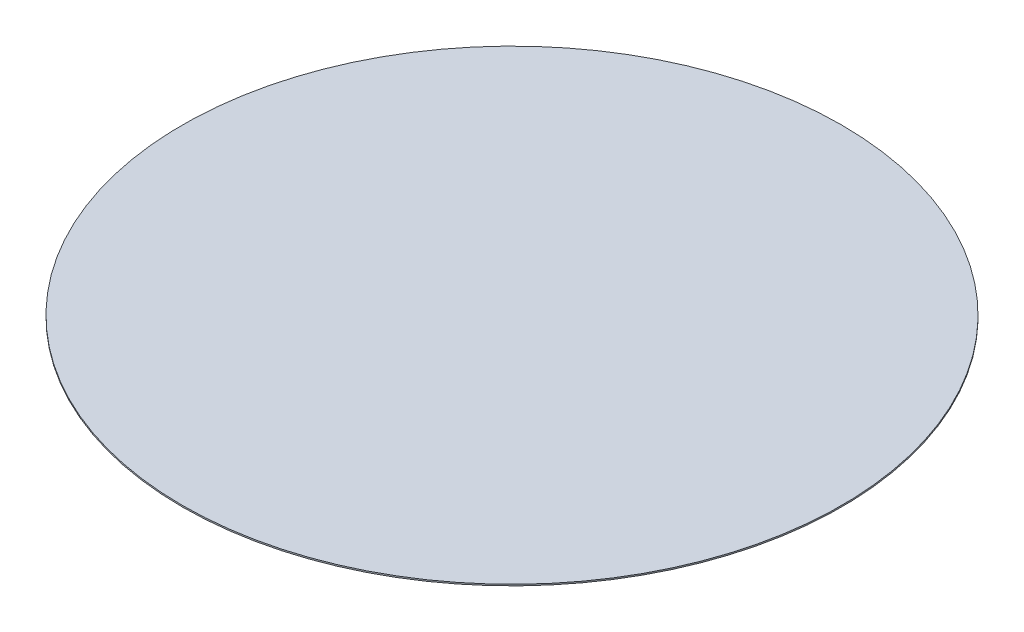
SolidWorks part; units mm, degrees
material "Ceramic Porcelain"
ref_plane "Front Plane" through (0, 0, 0) normal (0, 0, 1) x (1, 0, 0)
ref_plane "Top Plane" through (0, 0, 0) normal (0, 1, 0) x (1, 0, 0)
ref_plane "Right Plane" through (0, 0, 0) normal (1, 0, 0) x (0, 0, -1)
sketch "Sketch1" plane through (0, 0, 0) normal (0, 1, 0) x (1, 0, 0)
  circle A0 centre (0, 0) radius 140
  dimension "D1" = 280
extrude "Boss-Extrude1" add sketch "Sketch1" along normal blind 0.6 contours A0
